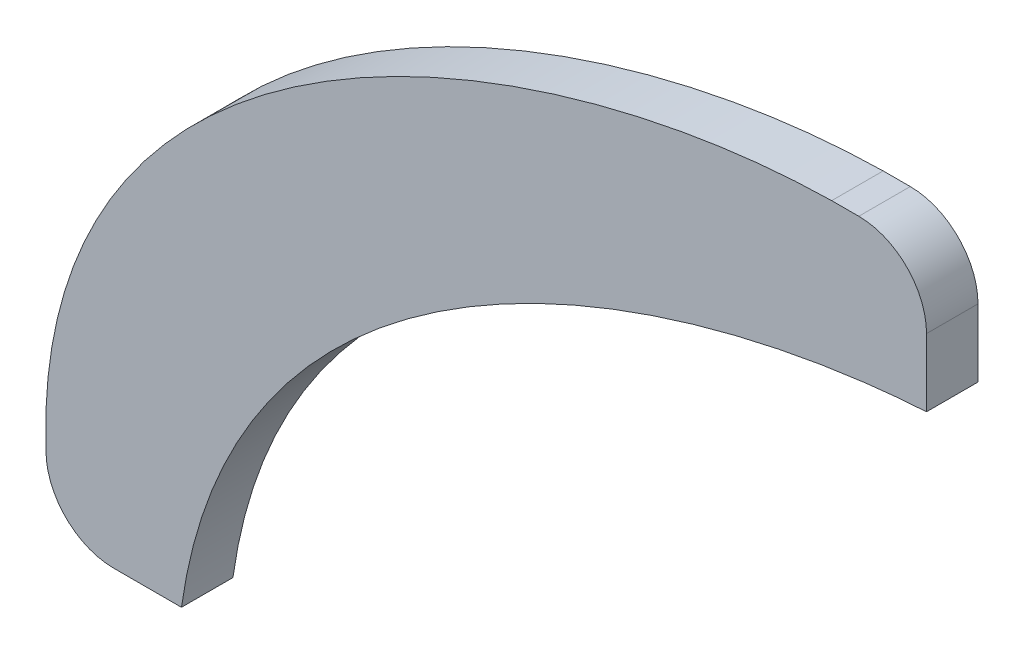
SolidWorks part; units mm, degrees
ref_plane "Front Plane" through (0, 0, 0) normal (0, 0, 1) x (1, 0, 0)
ref_plane "Top Plane" through (0, 0, 0) normal (0, 1, 0) x (1, 0, 0)
ref_plane "Right Plane" through (0, 0, 0) normal (1, 0, 0) x (0, 0, -1)
sketch "Sketch1" plane through (0, 0, 0) normal (0, 0, 1) x (1, 0, 0)
  line L1 (6.35, 0) -> (82.55, 0)
  line L2 (0, 6.35) -> (0, 63.5)
  line L3 (0, 63.5) -> (76.2, 63.5)
  line L4 (82.55, 0) -> (82.55, 57.15)
  arc A0 (82.55, 57.15) -> (76.2, 63.5) centre (76.2, 57.15) ccw
  arc A1 (0, 6.35) -> (6.35, 0) centre (6.35, 6.35) ccw
  spline S0 degree 3 poles (0, 6.35) (-1.4343, 43.9963) (45.0346, 64.052) (76.2, 63.5) knots 0 0 0 0 1 1 1 1
  spline S1 degree 3 poles (12.7, 0) (17.2635, 32.9464) (53.3334, 49.0332) (82.55, 50.8) knots 0 0 0 0 1 1 1 1
  point P7 (82.55, 63.5)
  point P10 (0, 0)
  dimension "D3" = 6.35
  dimension "D4" = 12.7
  dimension "D1" = 82.55
  dimension "D2" = 63.5
  dimension "D5" = 12.7
extrude "Boss-Extrude1" add sketch "Sketch1" along normal blind 4.826 contours L1 S1 L4 A0 L3 S0 L2 A1
equation "\"MDF\"= 0.19in"
equation "\"PVCID\" = 2.067in"
equation "\"PVCOD\" = 2.375in"
equation "\"GenDiameter\"= 60mm"
equation "\"GenCutDiameter\" = 1.8in"
equation "\"GenCutDistance\" = 1"
equation "\"TowerHeight\" = 6in"
equation "\"TowerFrontBase\" = 3in"
equation "\"FunnelHeight\" = 1in"
equation "\"FunnelAngle\" = 20"
equation "\"TowerSideBase\" = 3in"
equation "\"TowerPanelLength\" = 2in"
equation "\"TowerPanelLeeway\" = 0.5in"
equation "\"BaseLength\" = 9in"
equation "\"BaseWidth\" = 10in"
equation "\"WheelHoleLength\" = 3.25in"
equation "\"WheelHoleWidth\" = 26mm"
equation "\"WheelHoleFromBack\" = 1.5in"
equation "\"DropLength\" = 1in"
equation "\"DropWidth\" = 8.5in"
equation "\"BumperWidth\" = 1in"
equation "\"SmallHexDiameter\" = 0.185in"
equation "\"SmallHexHeight\" = 0.701in"
equation "\"ScrewSize\" = 0.106in"
equation "\"BigHexDiameter\" = 0.251in"
equation "\"BigHexHeight\" = 0.374in"
equation "\"PCBThickness\" = 0.066in"
equation "\"ConnectorHeight\" = 0.517in"
equation "\"BoardHeight\" = 0.583in"
equation "\"UnoStackHeight\" = 1.351in"
equation "\"UnoStackWidth\" = 3.053in"
equation "\"UnoStackLength\" = 3.152in"
equation "\"HBridgeWidth\" = 1.797in"
equation "\"HBridgeLength\" = 2.236in"
equation "\"DSWidth\" = 1.820in"
equation "\"DSLength\" = 1.833in"
equation "\"StepperWidth\" = 1.799in"
equation "\"StepperLength\" = 2.248in"
equation "\"ULNWidth\" = 1.304in"
equation "\"ULNLength\" = 1.545in"
equation "\"VSwitchHeight\" = 0.392in"
equation "\"VSwitchWidth\" = 0.637in"
equation "\"VSwitchLength\" = 1.097in"
equation "\"SkateWheelDiameter\" = 80mm"
equation "\"SkateWheelThickness\" = 24mm"
equation "\"BaseDistance\" = 3in"
equation "\"DummyVar\" = 2in"
equation "\"D1@Boss-Extrude1\"=\"MDF\""
